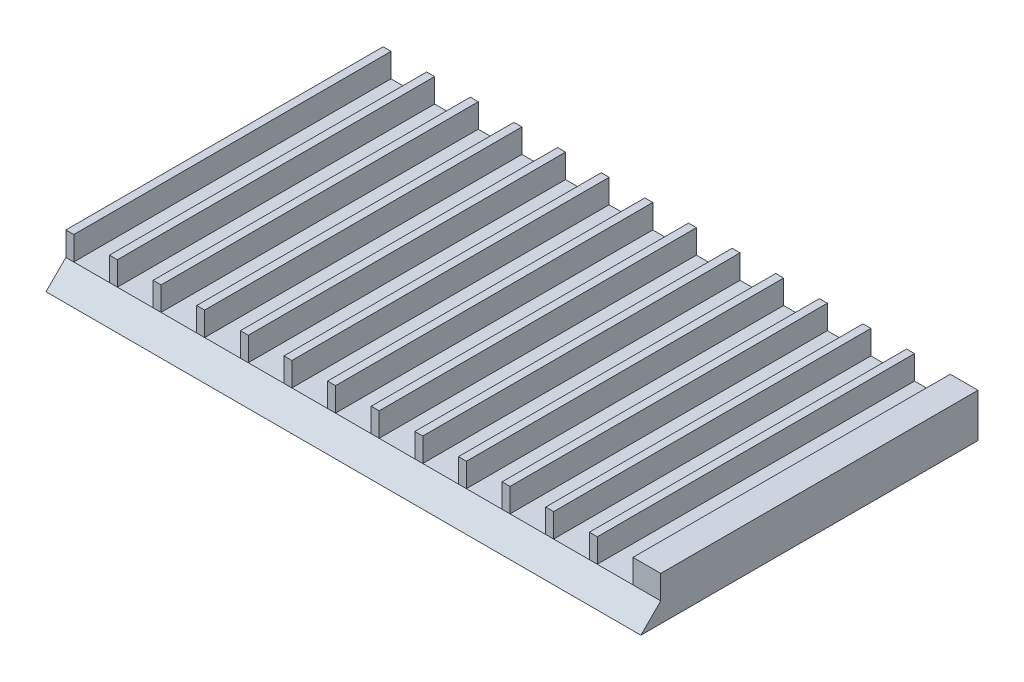
SolidWorks part; units mm, degrees
ref_plane "Front Plane" through (0, 0, 0) normal (0, 0, 1) x (1, 0, 0)
ref_plane "Top Plane" through (0, 0, 0) normal (0, 1, 0) x (1, 0, 0)
ref_plane "Right Plane" through (0, 0, 0) normal (1, 0, 0) x (0, 0, -1)
sketch "Sketch1" plane through (0, 0, 0) normal (0, 1, 0) x (1, 0, 0)
  line L1 (0, 0) -> (150, 0)
  line L2 (0, 0) -> (0, 80)
  line L3 (0, 80) -> (150, 80)
  line L4 (150, 0) -> (150, 80)
  point P4 (0, 0)
  dimension "D1" = 80
  dimension "D2" = 150
extrude "Boss-Extrude1" add sketch "Sketch1" along normal blind 5
sketch "Sketch2" plane through (0, 5, 0) normal (0, 1, 0) x (1, 0, 0)
  line L0 (0, 80) -> (0, 0)
  line L1 (0, 0) -> (2, 0)
  line L2 (0, 0) -> (150, 0) construction
  line L3 (2, 0) -> (2, 80)
  line L4 (150, 80) -> (0, 80) construction
  line L5 (2, 80) -> (0, 80)
  line L7 (13, 80) -> (11, 80)
  line L8 (11, 80) -> (11, 0)
  line L9 (11, 0) -> (13, 0)
  line L10 (13, 0) -> (13, 80)
  line L11 (24, 80) -> (22, 80)
  line L12 (22, 80) -> (22, 0)
  line L13 (22, 0) -> (24, 0)
  line L14 (24, 0) -> (24, 80)
  line L15 (35, 80) -> (33, 80)
  line L16 (33, 80) -> (33, 0)
  line L17 (33, 0) -> (35, 0)
  line L18 (35, 0) -> (35, 80)
  line L19 (46, 80) -> (44, 80)
  line L20 (44, 80) -> (44, 0)
  line L21 (44, 0) -> (46, 0)
  line L22 (46, 0) -> (46, 80)
  line L23 (57, 80) -> (55, 80)
  line L24 (55, 80) -> (55, 0)
  line L25 (55, 0) -> (57, 0)
  line L26 (57, 0) -> (57, 80)
  line L27 (68, 80) -> (66, 80)
  line L28 (66, 80) -> (66, 0)
  line L29 (66, 0) -> (68, 0)
  line L30 (68, 0) -> (68, 80)
  line L31 (79, 80) -> (77, 80)
  line L32 (77, 80) -> (77, 0)
  line L33 (77, 0) -> (79, 0)
  line L34 (79, 0) -> (79, 80)
  line L35 (90, 80) -> (88, 80)
  line L36 (88, 80) -> (88, 0)
  line L37 (88, 0) -> (90, 0)
  line L38 (90, 0) -> (90, 80)
  line L39 (101, 80) -> (99, 80)
  line L40 (99, 80) -> (99, 0)
  line L41 (99, 0) -> (101, 0)
  line L42 (101, 0) -> (101, 80)
  line L43 (112, 80) -> (110, 80)
  line L44 (110, 80) -> (110, 0)
  line L45 (110, 0) -> (112, 0)
  line L46 (112, 0) -> (112, 80)
  line L47 (123, 80) -> (121, 80)
  line L48 (121, 80) -> (121, 0)
  line L49 (121, 0) -> (123, 0)
  line L50 (123, 0) -> (123, 80)
  line L51 (134, 80) -> (132, 80)
  line L52 (132, 80) -> (132, 0)
  line L53 (132, 0) -> (134, 0)
  line L54 (134, 0) -> (134, 80)
  line L56 (143, 80) -> (143, 0)
  line L59 (145, 80) -> (143, 80) [skipped]
  line L60 (145, 0) -> (145, 80) [skipped]
  line L61 (143, 0) -> (145, 0) [skipped]
  line L62 (143, 0) -> (150, 0)
  line L63 (150, 0) -> (150, 80)
  line L64 (150, 80) -> (143, 80)
  dimension "D1" = 2
extrude "Boss-Extrude2" add sketch "Sketch2" along normal blind 6
sketch "Sketch3" plane through (0, 0, 0) normal (-1, 0, 0) x (0, 0, 1)
  line L0 (0, 0) -> (0, 5)
  line L1 (0, 5) -> (5, 0)
  line L2 (5, 0) -> (0, 0)
  dimension "D1" = 45
extrude "Boss-Extrude3" add sketch "Sketch3" against normal up to surface (150 mm away) up to face at (150, 5.5, -40)
